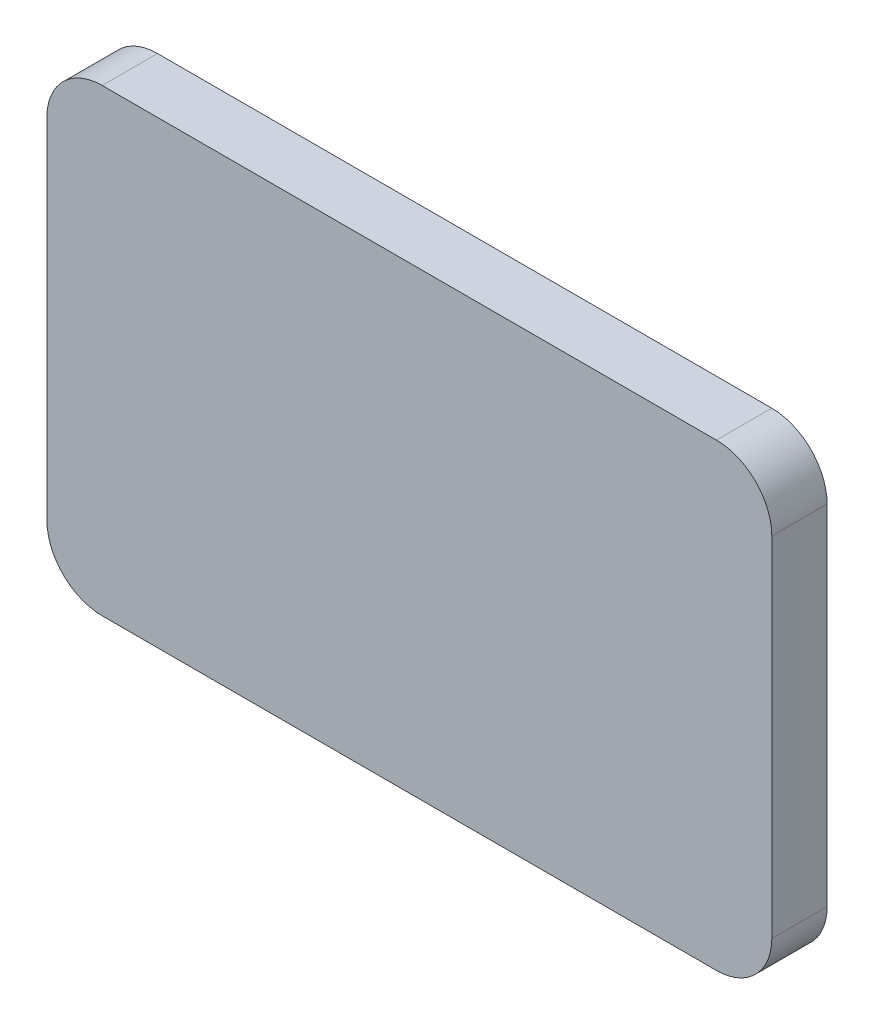
SolidWorks part; units mm, degrees
ref_plane "Plan de face" through (0, 0, 0) normal (0, 0, 1) x (1, 0, 0)
ref_plane "Plan de dessus" through (0, 0, 0) normal (0, 1, 0) x (1, 0, 0)
ref_plane "Plan de droite" through (0, 0, 0) normal (1, 0, 0) x (0, 0, -1)
sketch "Esquisse1" plane through (0, 0, 0) normal (0, 0, 1) x (1, 0, 0)
  line L1 (-32.75, 20.75) -> (32.75, 20.75)
  line L2 (-32.75, 20.75) -> (-32.75, -20.75)
  line L3 (-32.75, -20.75) -> (32.75, -20.75)
  line L4 (32.75, 20.75) -> (32.75, -20.75)
  line L5 (-32.75, 20.75) -> (32.75, -20.75) construction
  line L6 (-32.75, -20.75) -> (32.75, 20.75) construction
  point P0 (0, 0)
  dimension "D1" = 41.5
  dimension "D2" = 65.5
extrude "Boss.-Extru.1" add sketch "Esquisse1" along normal blind 5
shell "Coque1" thickness 3
fillet "Congé1" radius 5 8 edges at (32.75, -20.75, 2.5) (32.75, 20.75, 2.5) (-32.75, 20.75, 2.5) (-32.75, -20.75, 2.5) (-29.75, -17.75, 1) (-29.75, 17.75, 1) (29.75, 17.75, 1) (29.75, -17.75, 1)
